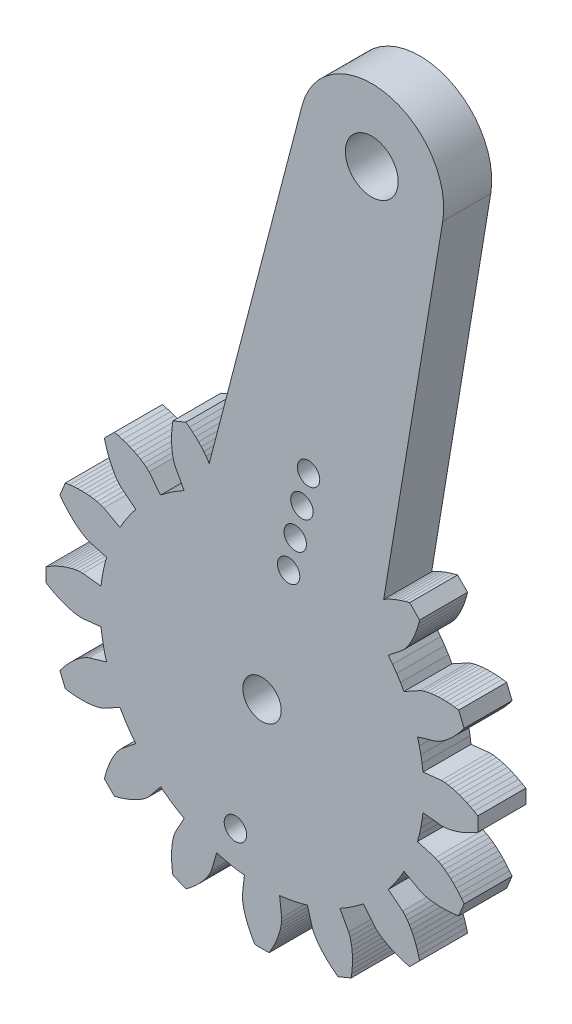
SolidWorks part; units mm, degrees
ref_plane "Спереди" through (0, 0, 0) normal (0, 0, 1) x (1, 0, 0)
ref_plane "Сверху" through (0, 0, 0) normal (0, 1, 0) x (1, 0, 0)
ref_plane "Справа" through (0, 0, 0) normal (1, 0, 0) x (0, 0, -1)
other "Configuration Table"
sketch "Eskiz_kontur" plane through (0, 0, 0) normal (0, 0, 1) x (1, 0, 0)
  line L0 (1.935, 1.1006) -> (1.9927, 1.5394)
  line L1 (1.9927, 1.5394) -> (2.0696, 1.9753)
  line L2 (0.7905, 1.2257) -> (1.935, 1.1006)
  line L3 (2.0696, 1.9753) -> (2.1654, 2.4074)
  line L4 (0.5663, 1.2203) -> (0.7905, 1.2257)
  line L5 (2.1654, 2.4074) -> (2.28, 2.8349)
  line L6 (0.3395, 1.1895) -> (0.5663, 1.2203)
  line L7 (2.28, 2.8349) -> (1.1747, 3.1573)
  line L8 (0.1112, 1.1412) -> (0.3395, 1.1895)
  line L9 (1.1747, 3.1573) -> (0.9696, 3.2481)
  line L10 (-0.1179, 1.078) -> (0.1112, 1.1412)
  line L11 (0.9696, 3.2481) -> (0.7719, 3.3634)
  line L12 (-0.3476, 1.0015) -> (-0.1179, 1.078)
  line L13 (0.7719, 3.3634) -> (0.5795, 3.4953)
  line L14 (-0.5775, 0.9126) -> (-0.3476, 1.0015)
  line L15 (0.5795, 3.4953) -> (0.3919, 3.6414)
  line L16 (-0.8072, 0.8118) -> (-0.5775, 0.9126)
  line L17 (0.3919, 3.6414) -> (0.209, 3.7999)
  line L18 (-1.0365, 0.6998) -> (-0.8072, 0.8118)
  line L19 (0.209, 3.7999) -> (0.0307, 3.97)
  line L20 (-1.2651, 0.5767) -> (-1.0365, 0.6998)
  line L21 (0.0307, 3.97) -> (-0.143, 4.151)
  line L22 (-1.4927, 0.443) -> (-1.2651, 0.5767)
  line L23 (-0.143, 4.151) -> (-0.3119, 4.3424)
  line L24 (-1.4927, -0.443) -> (-1.4927, 0.443)
  line L25 (-0.3119, 4.3424) -> (-0.476, 4.5435)
  line L26 (-1.2651, -0.5767) -> (-1.4927, -0.443)
  line L27 (-0.476, 4.5435) -> (-0.6352, 4.7542)
  line L28 (-1.0365, -0.6998) -> (-1.2651, -0.5767)
  line L29 (-0.6352, 4.7542) -> (-0.2962, 5.5727)
  line L30 (-0.8072, -0.8118) -> (-1.0365, -0.6998)
  line L31 (-0.2962, 5.5727) -> (-0.0347, 5.6091)
  line L32 (-0.5775, -0.9126) -> (-0.8072, -0.8118)
  line L33 (-0.0347, 5.6091) -> (0.2236, 5.6353)
  line L34 (-0.3476, -1.0015) -> (-0.5775, -0.9126)
  line L35 (0.2236, 5.6353) -> (0.4784, 5.6512)
  line L36 (-0.1179, -1.078) -> (-0.3476, -1.0015)
  line L37 (0.4784, 5.6512) -> (0.7292, 5.6563)
  line L38 (0.1112, -1.1412) -> (-0.1179, -1.078)
  line L39 (0.7292, 5.6563) -> (0.9756, 5.6505)
  line L40 (0.3395, -1.1895) -> (0.1112, -1.1412)
  line L41 (0.9756, 5.6505) -> (1.217, 5.6333)
  line L42 (0.5663, -1.2203) -> (0.3395, -1.1895)
  line L43 (1.217, 5.6333) -> (1.4529, 5.6039)
  line L44 (0.7905, -1.2257) -> (0.5663, -1.2203)
  line L45 (1.4529, 5.6039) -> (1.6823, 5.5612)
  line L46 (1.935, -1.1006) -> (0.7905, -1.2257)
  line L47 (1.6823, 5.5612) -> (1.9036, 5.5029)
  line L48 (1.9927, -1.5394) -> (1.935, -1.1006)
  line L49 (1.9036, 5.5029) -> (2.1128, 5.4221)
  line L50 (2.0696, -1.9753) -> (1.9927, -1.5394)
  line L51 (2.1128, 5.4221) -> (3.1223, 4.8685)
  line L52 (2.1654, -2.4074) -> (2.0696, -1.9753)
  line L53 (3.1223, 4.8685) -> (3.3436, 5.2518)
  line L54 (2.28, -2.8349) -> (2.1654, -2.4074)
  line L55 (3.3436, 5.2518) -> (3.5814, 5.6251)
  line L56 (1.1747, -3.1573) -> (2.28, -2.8349)
  line L57 (3.5814, 5.6251) -> (3.8353, 5.9877)
  line L58 (0.9696, -3.2481) -> (1.1747, -3.1573)
  line L59 (3.8353, 5.9877) -> (4.1048, 6.3388)
  line L60 (0.7719, -3.3634) -> (0.9696, -3.2481)
  line L61 (4.1048, 6.3388) -> (3.207, 7.0596)
  line L62 (0.5795, -3.4953) -> (0.7719, -3.3634)
  line L63 (3.207, 7.0596) -> (3.0522, 7.222)
  line L64 (0.3919, -3.6414) -> (0.5795, -3.4953)
  line L65 (3.0522, 7.222) -> (2.9137, 7.4042)
  line L66 (0.209, -3.7999) -> (0.3919, -3.6414)
  line L67 (2.9137, 7.4042) -> (2.7864, 7.5997)
  line L68 (0.0307, -3.97) -> (0.209, -3.7999)
  line L69 (2.7864, 7.5997) -> (2.669, 7.8064)
  line L70 (-0.143, -4.151) -> (0.0307, -3.97)
  line L71 (2.669, 7.8064) -> (2.5607, 8.0229)
  line L72 (-0.3119, -4.3424) -> (-0.143, -4.151)
  line L73 (2.5607, 8.0229) -> (2.4611, 8.2483)
  line L74 (-0.476, -4.5435) -> (-0.3119, -4.3424)
  line L75 (2.4611, 8.2483) -> (2.3699, 8.482)
  line L76 (-0.6352, -4.7542) -> (-0.476, -4.5435)
  line L77 (2.3699, 8.482) -> (2.287, 8.7234)
  line L78 (-0.2962, -5.5727) -> (-0.6352, -4.7542)
  line L79 (2.287, 8.7234) -> (2.2124, 8.9721)
  line L80 (-0.0347, -5.6091) -> (-0.2962, -5.5727)
  line L81 (2.2124, 8.9721) -> (2.146, 9.2276)
  line L82 (0.2236, -5.6353) -> (-0.0347, -5.6091)
  line L83 (2.146, 9.2276) -> (2.7724, 9.854)
  line L84 (0.4784, -5.6512) -> (0.2236, -5.6353)
  line L85 (2.7724, 9.854) -> (3.0279, 9.7876)
  line L86 (0.7292, -5.6563) -> (0.4784, -5.6512)
  line L87 (3.0279, 9.7876) -> (3.2766, 9.713)
  line L88 (0.9756, -5.6505) -> (0.7292, -5.6563)
  line L89 (3.2766, 9.713) -> (3.518, 9.6301)
  line L90 (1.217, -5.6333) -> (0.9756, -5.6505)
  line L91 (3.518, 9.6301) -> (3.7517, 9.5389)
  line L92 (1.4529, -5.6039) -> (1.217, -5.6333)
  line L93 (3.7517, 9.5389) -> (3.9771, 9.4393)
  line L94 (1.6823, -5.5612) -> (1.4529, -5.6039)
  line L95 (3.9771, 9.4393) -> (4.1936, 9.331)
  line L96 (1.9036, -5.5029) -> (1.6823, -5.5612)
  line L97 (4.1936, 9.331) -> (4.4003, 9.2136)
  line L98 (2.1128, -5.4221) -> (1.9036, -5.5029)
  line L99 (4.4003, 9.2136) -> (4.5958, 9.0863)
  line L100 (3.1223, -4.8685) -> (2.1128, -5.4221)
  line L101 (4.5958, 9.0863) -> (4.778, 8.9477)
  line L102 (3.3436, -5.2518) -> (3.1223, -4.8685)
  line L103 (4.778, 8.9477) -> (4.9404, 8.793)
  line L104 (3.5814, -5.6251) -> (3.3436, -5.2518)
  line L105 (4.9404, 8.793) -> (5.6612, 7.8952)
  line L106 (3.8353, -5.9877) -> (3.5814, -5.6251)
  line L107 (5.6612, 7.8952) -> (6.0123, 8.1647)
  line L108 (4.1048, -6.3388) -> (3.8353, -5.9877)
  line L109 (6.0123, 8.1647) -> (6.3749, 8.4186)
  line L110 (3.207, -7.0596) -> (4.1048, -6.3388)
  line L111 (6.3749, 8.4186) -> (6.7482, 8.6564)
  line L112 (3.0522, -7.222) -> (3.207, -7.0596)
  line L113 (6.7482, 8.6564) -> (7.1315, 8.8777)
  line L114 (2.9137, -7.4042) -> (3.0522, -7.222)
  line L115 (7.1315, 8.8777) -> (6.5779, 9.8872)
  line L116 (2.7864, -7.5997) -> (2.9137, -7.4042)
  line L117 (6.5779, 9.8872) -> (6.4971, 10.0964)
  line L118 (2.669, -7.8064) -> (2.7864, -7.5997)
  line L119 (6.4971, 10.0964) -> (6.4388, 10.3178)
  line L120 (2.5607, -8.0229) -> (2.669, -7.8064)
  line L121 (6.4388, 10.3178) -> (6.3961, 10.5471)
  line L122 (2.4611, -8.2483) -> (2.5607, -8.0229)
  line L123 (6.3961, 10.5471) -> (6.3667, 10.783)
  line L124 (2.3699, -8.482) -> (2.4611, -8.2483)
  line L125 (6.3667, 10.783) -> (6.3495, 11.0244)
  line L126 (2.287, -8.7234) -> (2.3699, -8.482)
  line L127 (6.3495, 11.0244) -> (6.3437, 11.2708)
  line L128 (2.2124, -8.9721) -> (2.287, -8.7234)
  line L129 (6.3437, 11.2708) -> (6.3488, 11.5216)
  line L130 (2.146, -9.2276) -> (2.2124, -8.9721)
  line L131 (6.3488, 11.5216) -> (6.3647, 11.7764)
  line L132 (2.7724, -9.854) -> (2.146, -9.2276)
  line L133 (6.3647, 11.7764) -> (6.3909, 12.0347)
  line L134 (3.0279, -9.7876) -> (2.7724, -9.854)
  line L135 (6.3909, 12.0347) -> (6.4273, 12.2962)
  line L136 (3.2766, -9.713) -> (3.0279, -9.7876)
  line L137 (6.4273, 12.2962) -> (7.2458, 12.6352)
  line L138 (3.518, -9.6301) -> (3.2766, -9.713)
  line L139 (7.2458, 12.6352) -> (7.4565, 12.4761)
  line L140 (3.7517, -9.5389) -> (3.518, -9.6301)
  line L141 (7.4565, 12.4761) -> (7.6576, 12.3119)
  line L142 (3.9771, -9.4393) -> (3.7517, -9.5389)
  line L143 (7.6576, 12.3119) -> (7.849, 12.143)
  line L144 (4.1936, -9.331) -> (3.9771, -9.4393)
  line L145 (7.849, 12.143) -> (8.03, 11.9693)
  line L146 (4.4003, -9.2136) -> (4.1936, -9.331)
  line L147 (8.03, 11.9693) -> (8.2001, 11.791)
  line L148 (4.5958, -9.0863) -> (4.4003, -9.2136)
  line L149 (8.2001, 11.791) -> (8.3587, 11.6081)
  line L150 (4.778, -8.9477) -> (4.5958, -9.0863)
  line L151 (8.3587, 11.6081) -> (8.5047, 11.4205)
  line L152 (4.9404, -8.793) -> (4.778, -8.9477)
  line L153 (8.5047, 11.4205) -> (8.6366, 11.2281)
  line L154 (5.6612, -7.8952) -> (4.9404, -8.793)
  line L155 (8.6366, 11.2281) -> (8.698, 11.1228)
  line L156 (6.0123, -8.1647) -> (5.6612, -7.8952)
  line L157 (8.698, 11.1228) -> (14.5044, 33.4056)
  line L158 (6.3749, -8.4186) -> (6.0123, -8.1647)
  line L159 (6.7482, -8.6564) -> (6.3749, -8.4186)
  line L160 (23.2994, 31.5362) -> (19.6066, 9.2175)
  line L161 (7.1315, -8.8777) -> (6.7482, -8.6564)
  line L162 (19.6066, 9.2175) -> (19.8064, 9.331)
  line L163 (6.5779, -9.8872) -> (7.1315, -8.8777)
  line L164 (19.8064, 9.331) -> (20.0229, 9.4393)
  line L165 (6.4971, -10.0964) -> (6.5779, -9.8872)
  line L166 (20.0229, 9.4393) -> (20.2483, 9.5389)
  line L167 (6.4388, -10.3178) -> (6.4971, -10.0964)
  line L168 (20.2483, 9.5389) -> (20.482, 9.6301)
  line L169 (6.3961, -10.5471) -> (6.4388, -10.3178)
  line L170 (20.482, 9.6301) -> (20.7234, 9.713)
  line L171 (6.3667, -10.783) -> (6.3961, -10.5471)
  line L172 (20.7234, 9.713) -> (20.9721, 9.7876)
  line L173 (6.3495, -11.0244) -> (6.3667, -10.783)
  line L174 (20.9721, 9.7876) -> (21.2276, 9.854)
  line L175 (6.3437, -11.2708) -> (6.3495, -11.0244)
  line L176 (21.2276, 9.854) -> (21.854, 9.2276)
  line L177 (6.3488, -11.5216) -> (6.3437, -11.2708)
  line L178 (21.854, 9.2276) -> (21.7876, 8.9721)
  line L179 (6.3647, -11.7764) -> (6.3488, -11.5216)
  line L180 (21.7876, 8.9721) -> (21.713, 8.7234)
  line L181 (6.3909, -12.0347) -> (6.3647, -11.7764)
  line L182 (21.713, 8.7234) -> (21.6301, 8.482)
  line L183 (6.4273, -12.2962) -> (6.3909, -12.0347)
  line L184 (21.6301, 8.482) -> (21.5389, 8.2483)
  line L185 (7.2458, -12.6352) -> (6.4273, -12.2962)
  line L186 (21.5389, 8.2483) -> (21.4393, 8.0229)
  line L187 (7.4565, -12.4761) -> (7.2458, -12.6352)
  line L188 (21.4393, 8.0229) -> (21.331, 7.8064)
  line L189 (7.6576, -12.3119) -> (7.4565, -12.4761)
  line L190 (21.331, 7.8064) -> (21.2136, 7.5997)
  line L191 (7.849, -12.143) -> (7.6576, -12.3119)
  line L192 (21.2136, 7.5997) -> (21.0863, 7.4042)
  line L193 (8.03, -11.9693) -> (7.849, -12.143)
  line L194 (21.0863, 7.4042) -> (20.9477, 7.222)
  line L195 (8.2001, -11.791) -> (8.03, -11.9693)
  line L196 (20.9477, 7.222) -> (20.793, 7.0596)
  line L197 (8.3587, -11.6081) -> (8.2001, -11.791)
  line L198 (20.793, 7.0596) -> (19.8953, 6.3388)
  line L199 (8.5047, -11.4205) -> (8.3587, -11.6081)
  line L200 (19.8953, 6.3388) -> (20.1647, 5.9877)
  line L201 (8.6366, -11.2281) -> (8.5047, -11.4205)
  line L202 (20.1647, 5.9877) -> (20.4186, 5.6251)
  line L203 (8.7519, -11.0304) -> (8.6366, -11.2281)
  line L204 (20.4186, 5.6251) -> (20.6564, 5.2518)
  line L205 (8.8427, -10.8253) -> (8.7519, -11.0304)
  line L206 (20.6564, 5.2518) -> (20.8777, 4.8685)
  line L207 (9.1651, -9.72) -> (8.8427, -10.8253)
  line L208 (20.8777, 4.8685) -> (21.8872, 5.4221)
  line L209 (9.5926, -9.8346) -> (9.1651, -9.72)
  line L210 (21.8872, 5.4221) -> (22.0964, 5.5029)
  line L211 (10.0247, -9.9305) -> (9.5926, -9.8346)
  line L212 (22.0964, 5.5029) -> (22.3178, 5.5612)
  line L213 (10.4606, -10.0073) -> (10.0247, -9.9305)
  line L214 (22.3178, 5.5612) -> (22.5471, 5.6039)
  line L215 (10.8994, -10.065) -> (10.4606, -10.0073)
  line L216 (22.5471, 5.6039) -> (22.783, 5.6333)
  line L217 (10.7743, -11.2095) -> (10.8994, -10.065)
  line L218 (22.783, 5.6333) -> (23.0244, 5.6505)
  line L219 (10.7797, -11.4337) -> (10.7743, -11.2095)
  line L220 (23.0244, 5.6505) -> (23.2708, 5.6563)
  line L221 (10.8105, -11.6605) -> (10.7797, -11.4337)
  line L222 (23.2708, 5.6563) -> (23.5216, 5.6512)
  line L223 (10.8588, -11.8888) -> (10.8105, -11.6605)
  line L224 (23.5216, 5.6512) -> (23.7764, 5.6353)
  line L225 (10.922, -12.1179) -> (10.8588, -11.8888)
  line L226 (23.7764, 5.6353) -> (24.0347, 5.6091)
  line L227 (10.9985, -12.3476) -> (10.922, -12.1179)
  line L228 (24.0347, 5.6091) -> (24.2962, 5.5727)
  line L229 (11.0874, -12.5775) -> (10.9985, -12.3476)
  line L230 (24.2962, 5.5727) -> (24.6352, 4.7542)
  line L231 (11.1882, -12.8072) -> (11.0874, -12.5775)
  line L232 (24.6352, 4.7542) -> (24.4761, 4.5435)
  line L233 (11.3002, -13.0365) -> (11.1882, -12.8072)
  line L234 (24.4761, 4.5435) -> (24.3119, 4.3424)
  line L235 (11.4233, -13.2651) -> (11.3002, -13.0365)
  line L236 (24.3119, 4.3424) -> (24.143, 4.151)
  line L237 (11.5571, -13.4927) -> (11.4233, -13.2651)
  line L238 (24.143, 4.151) -> (23.9693, 3.97)
  line L239 (12.4429, -13.4927) -> (11.5571, -13.4927)
  line L240 (23.9693, 3.97) -> (23.791, 3.7999)
  line L241 (12.5767, -13.2651) -> (12.4429, -13.4927)
  line L242 (23.791, 3.7999) -> (23.6081, 3.6414)
  line L243 (12.6998, -13.0365) -> (12.5767, -13.2651)
  line L244 (23.6081, 3.6414) -> (23.4205, 3.4953)
  line L245 (12.8118, -12.8072) -> (12.6998, -13.0365)
  line L246 (23.4205, 3.4953) -> (23.2281, 3.3634)
  line L247 (12.9126, -12.5775) -> (12.8118, -12.8072)
  line L248 (23.2281, 3.3634) -> (23.0304, 3.2481)
  line L249 (13.0015, -12.3476) -> (12.9126, -12.5775)
  line L250 (23.0304, 3.2481) -> (22.8253, 3.1573)
  line L251 (13.078, -12.1179) -> (13.0015, -12.3476)
  line L252 (22.8253, 3.1573) -> (21.72, 2.8349)
  line L253 (13.1412, -11.8888) -> (13.078, -12.1179)
  line L254 (21.72, 2.8349) -> (21.8346, 2.4074)
  line L255 (13.1895, -11.6605) -> (13.1412, -11.8888)
  line L256 (21.8346, 2.4074) -> (21.9305, 1.9753)
  line L257 (13.2203, -11.4337) -> (13.1895, -11.6605)
  line L258 (21.9305, 1.9753) -> (22.0073, 1.5394)
  line L259 (13.2257, -11.2095) -> (13.2203, -11.4337)
  line L260 (22.0073, 1.5394) -> (22.065, 1.1006)
  line L261 (13.1006, -10.065) -> (13.2257, -11.2095)
  line L262 (22.065, 1.1006) -> (23.2095, 1.2257)
  line L263 (13.5394, -10.0073) -> (13.1006, -10.065)
  line L264 (23.2095, 1.2257) -> (23.4337, 1.2203)
  line L265 (13.9753, -9.9305) -> (13.5394, -10.0073)
  line L266 (23.4337, 1.2203) -> (23.6605, 1.1895)
  line L267 (14.4074, -9.8346) -> (13.9753, -9.9305)
  line L268 (23.6605, 1.1895) -> (23.8888, 1.1412)
  line L269 (14.8349, -9.72) -> (14.4074, -9.8346)
  line L270 (23.8888, 1.1412) -> (24.1179, 1.078)
  line L271 (15.1573, -10.8253) -> (14.8349, -9.72)
  line L272 (24.1179, 1.078) -> (24.3476, 1.0015)
  line L273 (15.2481, -11.0304) -> (15.1573, -10.8253)
  line L274 (24.3476, 1.0015) -> (24.5775, 0.9126)
  line L275 (15.3634, -11.2281) -> (15.2481, -11.0304)
  line L276 (24.5775, 0.9126) -> (24.8072, 0.8118)
  line L277 (15.4953, -11.4205) -> (15.3634, -11.2281)
  line L278 (24.8072, 0.8118) -> (25.0365, 0.6998)
  line L279 (15.6413, -11.6081) -> (15.4953, -11.4205)
  line L280 (25.0365, 0.6998) -> (25.2651, 0.5767)
  line L281 (15.7999, -11.791) -> (15.6413, -11.6081)
  line L282 (25.2651, 0.5767) -> (25.4927, 0.443)
  line L283 (15.97, -11.9693) -> (15.7999, -11.791)
  line L284 (25.4927, 0.443) -> (25.4927, -0.443)
  line L285 (16.1511, -12.143) -> (15.97, -11.9693)
  line L286 (25.4927, -0.443) -> (25.2651, -0.5767)
  line L287 (16.3424, -12.3119) -> (16.1511, -12.143)
  line L288 (25.2651, -0.5767) -> (25.0365, -0.6998)
  line L289 (16.5435, -12.4761) -> (16.3424, -12.3119)
  line L290 (25.0365, -0.6998) -> (24.8072, -0.8118)
  line L291 (16.7542, -12.6352) -> (16.5435, -12.4761)
  line L292 (24.8072, -0.8118) -> (24.5775, -0.9126)
  line L293 (17.5727, -12.2962) -> (16.7542, -12.6352)
  line L294 (24.5775, -0.9126) -> (24.3476, -1.0015)
  line L295 (17.6091, -12.0347) -> (17.5727, -12.2962)
  line L296 (24.3476, -1.0015) -> (24.1179, -1.078)
  line L297 (17.6353, -11.7764) -> (17.6091, -12.0347)
  line L298 (24.1179, -1.078) -> (23.8888, -1.1412)
  line L299 (17.6512, -11.5216) -> (17.6353, -11.7764)
  line L300 (23.8888, -1.1412) -> (23.6605, -1.1895)
  line L301 (17.6563, -11.2708) -> (17.6512, -11.5216)
  line L302 (23.6605, -1.1895) -> (23.4337, -1.2203)
  line L303 (17.6505, -11.0244) -> (17.6563, -11.2708)
  line L304 (23.4337, -1.2203) -> (23.2095, -1.2257)
  line L305 (17.6333, -10.783) -> (17.6505, -11.0244)
  line L306 (23.2095, -1.2257) -> (22.065, -1.1006)
  line L307 (17.6039, -10.5471) -> (17.6333, -10.783)
  line L308 (22.065, -1.1006) -> (22.0073, -1.5394)
  line L309 (17.5612, -10.3178) -> (17.6039, -10.5471)
  line L310 (22.0073, -1.5394) -> (21.9305, -1.9753)
  line L311 (17.5029, -10.0964) -> (17.5612, -10.3178)
  line L312 (21.9305, -1.9753) -> (21.8346, -2.4074)
  line L313 (17.4221, -9.8872) -> (17.5029, -10.0964)
  line L314 (21.8346, -2.4074) -> (21.72, -2.8349)
  line L315 (16.8685, -8.8777) -> (17.4221, -9.8872)
  line L316 (21.72, -2.8349) -> (22.8253, -3.1573)
  line L317 (17.2518, -8.6564) -> (16.8685, -8.8777)
  line L318 (22.8253, -3.1573) -> (23.0304, -3.2481)
  line L319 (17.6252, -8.4186) -> (17.2518, -8.6564)
  line L320 (23.0304, -3.2481) -> (23.2281, -3.3634)
  line L321 (17.9877, -8.1647) -> (17.6252, -8.4186)
  line L322 (23.2281, -3.3634) -> (23.4205, -3.4953)
  line L323 (18.3388, -7.8952) -> (17.9877, -8.1647)
  line L324 (23.4205, -3.4953) -> (23.6081, -3.6414)
  line L325 (19.0596, -8.793) -> (18.3388, -7.8952)
  line L326 (23.6081, -3.6414) -> (23.791, -3.7999)
  line L327 (19.222, -8.9477) -> (19.0596, -8.793)
  line L328 (23.791, -3.7999) -> (23.9693, -3.97)
  line L329 (19.4042, -9.0863) -> (19.222, -8.9477)
  line L330 (23.9693, -3.97) -> (24.143, -4.151)
  line L331 (19.5997, -9.2136) -> (19.4042, -9.0863)
  line L332 (24.143, -4.151) -> (24.3119, -4.3424)
  line L333 (19.8064, -9.331) -> (19.5997, -9.2136)
  line L334 (24.3119, -4.3424) -> (24.4761, -4.5435)
  line L335 (20.0229, -9.4393) -> (19.8064, -9.331)
  line L336 (24.4761, -4.5435) -> (24.6352, -4.7542)
  line L337 (20.2483, -9.5389) -> (20.0229, -9.4393)
  line L338 (24.6352, -4.7542) -> (24.2962, -5.5727)
  line L339 (20.482, -9.6301) -> (20.2483, -9.5389)
  line L340 (24.2962, -5.5727) -> (24.0347, -5.6091)
  line L341 (20.7234, -9.713) -> (20.482, -9.6301)
  line L342 (24.0347, -5.6091) -> (23.7764, -5.6353)
  line L343 (20.9721, -9.7876) -> (20.7234, -9.713)
  line L344 (23.7764, -5.6353) -> (23.5216, -5.6512)
  line L345 (21.2276, -9.854) -> (20.9721, -9.7876)
  line L346 (23.5216, -5.6512) -> (23.2708, -5.6563)
  line L347 (21.854, -9.2276) -> (21.2276, -9.854)
  line L348 (23.2708, -5.6563) -> (23.0244, -5.6505)
  line L349 (21.7876, -8.9721) -> (21.854, -9.2276)
  line L350 (23.0244, -5.6505) -> (22.783, -5.6333)
  line L351 (21.713, -8.7234) -> (21.7876, -8.9721)
  line L352 (22.783, -5.6333) -> (22.5471, -5.6039)
  line L353 (21.6301, -8.482) -> (21.713, -8.7234)
  line L354 (22.5471, -5.6039) -> (22.3178, -5.5612)
  line L355 (21.5389, -8.2483) -> (21.6301, -8.482)
  line L356 (22.3178, -5.5612) -> (22.0964, -5.5029)
  line L357 (21.4393, -8.0229) -> (21.5389, -8.2483)
  line L358 (22.0964, -5.5029) -> (21.8872, -5.4221)
  line L359 (21.331, -7.8064) -> (21.4393, -8.0229)
  line L360 (21.8872, -5.4221) -> (20.8777, -4.8685)
  line L361 (21.2136, -7.5997) -> (21.331, -7.8064)
  line L362 (20.8777, -4.8685) -> (20.6564, -5.2518)
  line L363 (21.0863, -7.4042) -> (21.2136, -7.5997)
  line L364 (20.6564, -5.2518) -> (20.4186, -5.6251)
  line L365 (20.9477, -7.222) -> (21.0863, -7.4042)
  line L366 (20.4186, -5.6251) -> (20.1647, -5.9877)
  line L367 (20.793, -7.0596) -> (20.9477, -7.222)
  line L368 (20.1647, -5.9877) -> (19.8953, -6.3388)
  line L369 (19.8953, -6.3388) -> (20.793, -7.0596)
  arc A0 (14.5044, 33.4056) -> (23.2994, 31.5362) centre (18.8611, 32.2789) cw
extrude "Plastina" add sketch "Eskiz_kontur" along normal blind 3
sketch "Eskiz_otverstiya" plane through (0, 0, 0) normal (0, 0, 1) x (1, 0, 0)
  circle A0 centre (10.3367, -7.8252) radius 0.7
  circle A1 centre (12, 0) radius 1.2
  circle A2 centre (13.6633, 7.8252) radius 0.7
  circle A3 centre (14.0791, 9.7815) radius 0.7
  circle A4 centre (14.4949, 11.7378) radius 0.7
  circle A5 centre (14.9108, 13.6941) radius 0.7
  circle A6 centre (18.8611, 32.2789) radius 1.65
  dimension "d1" = 1.4
  dimension "d2" = 2.4
  dimension "d3" = 1.4
  dimension "d4" = 1.4
  dimension "d5" = 1.4
  dimension "d6" = 1.4
  dimension "d7" = 3.3
extrude "Otverstiya" cut sketch "Eskiz_otverstiya" against normal through all and the other way through all
equation "\"T3\" = 3"
equation "\"T5\" = 5"
equation "\"D_M3\" = 3.3"
equation "\"D_M2\" = 2.2"
equation "\"D_M3_TAP\" = 2.5"
equation "\"D_M4\" = 4.5"
equation "\"L1\" = 100"
equation "\"L2\" = 100"
equation "\"D1@Plastina\" = \"T3\""
equation "\"d7@Eskiz_otverstiya\" = \"D_M3\""
